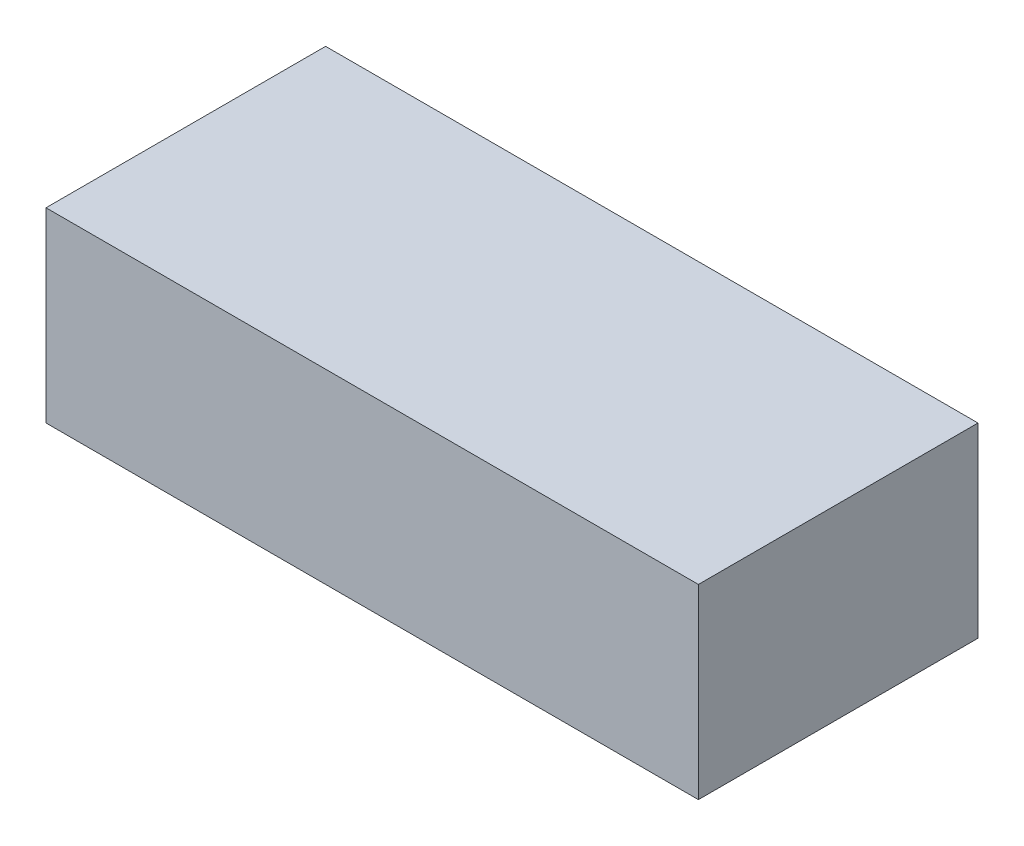
SolidWorks part; units mm, degrees
ref_plane "前视基准面" through (0, 0, 0) normal (0, 0, 1) x (1, 0, 0)
ref_plane "上视基准面" through (0, 0, 0) normal (0, 1, 0) x (1, 0, 0)
ref_plane "右视基准面" through (0, 0, 0) normal (1, 0, 0) x (0, 0, -1)
sketch "草图1" plane through (0, 0, 0) normal (0, 1, 0) x (1, 0, 0)
  line L1 (-14, 6) -> (14, 6)
  line L2 (-14, 6) -> (-14, -6)
  line L3 (-14, -6) -> (14, -6)
  line L4 (14, 6) -> (14, -6)
  line L5 (0, -6) -> (0, 6) construction
  line L6 (-14, 0) -> (14, 0) construction
  point P0 (0, 0)
  dimension "D1" = 28
  dimension "D2" = 12
extrude "凸台-拉伸1" add sketch "草图1" along normal blind 8
